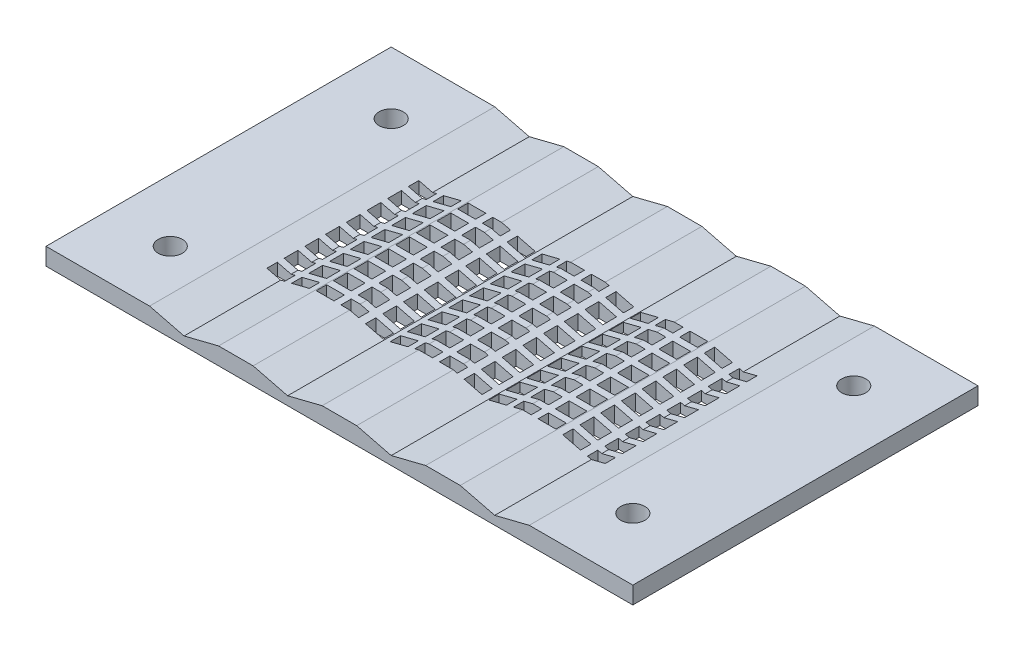
SolidWorks part; units mm, degrees
ref_plane "Front Plane" through (0, 0, 0) normal (0, 0, 1) x (1, 0, 0)
ref_plane "Top Plane" through (0, 0, 0) normal (0, 1, 0) x (1, 0, 0)
ref_plane "Right Plane" through (0, 0, 0) normal (1, 0, 0) x (0, 0, -1)
sketch "Sketch1" plane through (0, 0, 0) normal (0, 1, 0) x (1, 0, 0)
  line L1 (42.5, -25) -> (-42.5, -25)
  line L2 (42.5, -25) -> (42.5, 25)
  line L3 (42.5, 25) -> (-42.5, 25)
  line L4 (-42.5, -25) -> (-42.5, 25)
  line L5 (42.5, -25) -> (-42.5, 25) construction
  line L6 (42.5, 25) -> (-42.5, -25) construction
  point P0 (0, 0)
extrude "Base Plate" add sketch "Sketch1" along normal blind 2.5
sketch "Sketch7" plane through (0, 2.5, 0) normal (0, 1, 0) x (1, 0, 0)
  line L2 (0, 0) -> (-11.5051, 0) construction
  line L3 (-42.5, 25) -> (-42.5, -25) construction
  line L4 (0, 13.9859) -> (0, 0) construction
  line L5 (42.5, 25) -> (-42.5, 25) construction
  circle A0 centre (-33.5, 16) radius 1.75
  circle A1 centre (-33.5, -16) radius 1.75
  circle A2 centre (33.5, -16) radius 1.75
  circle A3 centre (33.5, 16) radius 1.75
  dimension "D1" = 3.5
  dimension "D2" = 9
  dimension "D3" = 9
extrude "Scre Cut" cut sketch "Sketch7" against normal blind 5
sketch "Sketch13" plane through (0, 2.5, 0) normal (0, 1, 0) x (1, 0, 0)
  line L1 (-24.5, 11) -> (24.5, 11)
  line L2 (-24.5, 11) -> (-24.5, -11)
  line L3 (-24.5, -11) -> (24.5, -11)
  line L4 (24.5, 11) -> (24.5, -11)
  line L5 (-24.5, 11) -> (24.5, -11) construction
  line L6 (-24.5, -11) -> (24.5, 11) construction
  line L8 (-42.5, -25) -> (42.5, -25) construction
  line L9 (42.5, -25) -> (42.5, 25) construction
  point P0 (0, 0)
  dimension "D1" = 14
  dimension "D2" = 18
extrude "Cut-Extrude1" cut sketch "Sketch13" against normal blind 10
sketch "Sketch14" plane through (0, 2.5, 0) normal (0, 1, 0) x (1, 0, 0)
  line L0 (-24.5, 0) -> (-22, 0) construction
  line L1 (-24.5, 11) -> (-24.5, -11) construction
  line L2 (-18.3571, -11) -> (-18.3571, -9.5)
  line L3 (-24.5, -11) -> (24.5, -11) construction
  line L4 (-21.9286, 0.5) -> (-21.9286, 2.5)
  line L5 (-24.5, -0.5) -> (-21.9286, -0.5)
  line L6 (-24.5, -0.5) -> (-24.5, 0.5)
  line L7 (-24.5, 0.5) -> (-21.9286, 0.5)
  line L8 (-20.9286, 9.5) -> (-20.9286, 11)
  line L9 (-20.9286, 6.5) -> (-20.9286, 8.5)
  line L10 (-20.9286, 3.5) -> (-20.9286, 5.5)
  line L11 (24.5, 11) -> (-24.5, 11) construction
  line L12 (-21.9286, -11) -> (-20.9286, -11)
  line L13 (-21.9286, -11) -> (-21.9286, -9.5)
  line L14 (-21.9286, 11) -> (-20.9286, 11)
  line L15 (-20.9286, -2.5) -> (-20.9286, -0.5)
  line L16 (-20.9286, -5.5) -> (-20.9286, -3.5)
  line L17 (-20.9286, -8.5) -> (-20.9286, -6.5)
  line L18 (-24.5, 2.5) -> (-24.5, 3.5)
  line L19 (-24.5, 2.5) -> (-21.9286, 2.5)
  line L20 (-24.5, 3.5) -> (-21.9286, 3.5)
  line L21 (-24.5, 5.5) -> (-24.5, 6.5)
  line L22 (-24.5, 5.5) -> (-21.9286, 5.5)
  line L23 (-24.5, 6.5) -> (-21.9286, 6.5)
  line L24 (-24.5, 8.5) -> (-24.5, 9.5)
  line L25 (-24.5, 8.5) -> (-21.9286, 8.5)
  line L26 (-24.5, 9.5) -> (-21.9286, 9.5)
  line L27 (-24.5, -3.5) -> (-21.9286, -3.5)
  line L28 (-24.5, -3.5) -> (-24.5, -2.5)
  line L29 (-24.5, -2.5) -> (-21.9286, -2.5)
  line L30 (-24.5, -6.5) -> (-21.9286, -6.5)
  line L31 (-24.5, -6.5) -> (-24.5, -5.5)
  line L32 (-24.5, -5.5) -> (-21.9286, -5.5)
  line L33 (-24.5, -9.5) -> (-21.9286, -9.5)
  line L34 (-24.5, -9.5) -> (-24.5, -8.5)
  line L35 (-24.5, -8.5) -> (-21.9286, -8.5)
  line L36 (-21.9286, -8.5) -> (-21.9286, -6.5)
  line L37 (-21.9286, -5.5) -> (-21.9286, -3.5)
  line L38 (-21.9286, -2.5) -> (-21.9286, -0.5)
  line L39 (-21.9286, 3.5) -> (-21.9286, 5.5)
  line L40 (-21.9286, 6.5) -> (-21.9286, 8.5)
  line L41 (-21.9286, 9.5) -> (-21.9286, 11)
  line L42 (-21.4286, 11) -> (-21.4286, 9.5) construction
  line L43 (-18.3571, -8.5) -> (-20.9286, -8.5)
  line L44 (-18.3571, -8.5) -> (-18.3571, -6.5)
  line L45 (-18.3571, -9.5) -> (-20.9286, -9.5)
  line L46 (-18.3571, -5.5) -> (-20.9286, -5.5)
  line L47 (-18.3571, -5.5) -> (-18.3571, -3.5)
  line L48 (-18.3571, -6.5) -> (-20.9286, -6.5)
  line L49 (-18.3571, -2.5) -> (-20.9286, -2.5)
  line L50 (-18.3571, -2.5) -> (-18.3571, -0.5)
  line L51 (-18.3571, -3.5) -> (-20.9286, -3.5)
  line L52 (-18.3571, 9.5) -> (-20.9286, 9.5)
  line L53 (-18.3571, 8.5) -> (-20.9286, 8.5)
  line L54 (-18.3571, 0.5) -> (-18.3571, 2.5)
  line L55 (-18.3571, 6.5) -> (-20.9286, 6.5)
  line L56 (-18.3571, 5.5) -> (-20.9286, 5.5)
  line L57 (-18.3571, 3.5) -> (-18.3571, 5.5)
  line L58 (-18.3571, 3.5) -> (-20.9286, 3.5)
  line L59 (-18.3571, 2.5) -> (-20.9286, 2.5)
  line L60 (-18.3571, 9.5) -> (-18.3571, 11)
  line L61 (-20.9286, -11) -> (-20.9286, -9.5)
  line L62 (-18.3571, 0.5) -> (-20.9286, 0.5)
  line L63 (-18.3571, 6.5) -> (-18.3571, 8.5)
  line L64 (-18.3571, -0.5) -> (-20.9286, -0.5)
  line L65 (-20.9286, 0.5) -> (-20.9286, 2.5)
  line L66 (-11.2143, -11) -> (-11.2143, -9.5)
  line L67 (-14.7857, 0.5) -> (-14.7857, 2.5)
  line L68 (-17.3571, -0.5) -> (-14.7857, -0.5)
  line L69 (-17.3571, 0.5) -> (-14.7857, 0.5)
  line L70 (-13.7857, 9.5) -> (-13.7857, 11)
  line L71 (-13.7857, 6.5) -> (-13.7857, 8.5)
  line L72 (-13.7857, 3.5) -> (-13.7857, 5.5)
  line L73 (-14.7857, -11) -> (-13.7857, -11)
  line L74 (-14.7857, -11) -> (-14.7857, -9.5)
  line L75 (-14.7857, 11) -> (-13.7857, 11)
  line L76 (-13.7857, -2.5) -> (-13.7857, -0.5)
  line L77 (-13.7857, -5.5) -> (-13.7857, -3.5)
  line L78 (-13.7857, -8.5) -> (-13.7857, -6.5)
  line L79 (-17.3571, 2.5) -> (-14.7857, 2.5)
  line L80 (-17.3571, 3.5) -> (-14.7857, 3.5)
  line L81 (-17.3571, 5.5) -> (-14.7857, 5.5)
  line L82 (-17.3571, 6.5) -> (-14.7857, 6.5)
  line L83 (-17.3571, 8.5) -> (-14.7857, 8.5)
  line L84 (-17.3571, 9.5) -> (-14.7857, 9.5)
  line L85 (-17.3571, -3.5) -> (-14.7857, -3.5)
  line L86 (-17.3571, -2.5) -> (-14.7857, -2.5)
  line L87 (-17.3571, -6.5) -> (-14.7857, -6.5)
  line L88 (-17.3571, -5.5) -> (-14.7857, -5.5)
  line L89 (-17.3571, -9.5) -> (-14.7857, -9.5)
  line L90 (-17.3571, -8.5) -> (-14.7857, -8.5)
  line L91 (-14.7857, -8.5) -> (-14.7857, -6.5)
  line L92 (-14.7857, -5.5) -> (-14.7857, -3.5)
  line L93 (-14.7857, -2.5) -> (-14.7857, -0.5)
  line L94 (-14.7857, 3.5) -> (-14.7857, 5.5)
  line L95 (-14.7857, 6.5) -> (-14.7857, 8.5)
  line L96 (-14.7857, 9.5) -> (-14.7857, 11)
  line L97 (-11.2143, -8.5) -> (-13.7857, -8.5)
  line L98 (-11.2143, -8.5) -> (-11.2143, -6.5)
  line L99 (-11.2143, -9.5) -> (-13.7857, -9.5)
  line L100 (-11.2143, -5.5) -> (-13.7857, -5.5)
  line L101 (-11.2143, -5.5) -> (-11.2143, -3.5)
  line L102 (-11.2143, -6.5) -> (-13.7857, -6.5)
  line L103 (-11.2143, -2.5) -> (-13.7857, -2.5)
  line L104 (-11.2143, -2.5) -> (-11.2143, -0.5)
  line L105 (-11.2143, -3.5) -> (-13.7857, -3.5)
  line L106 (-11.2143, 9.5) -> (-13.7857, 9.5)
  line L107 (-11.2143, 8.5) -> (-13.7857, 8.5)
  line L108 (-11.2143, 0.5) -> (-11.2143, 2.5)
  line L109 (-11.2143, 6.5) -> (-13.7857, 6.5)
  line L110 (-11.2143, 5.5) -> (-13.7857, 5.5)
  line L111 (-11.2143, 3.5) -> (-11.2143, 5.5)
  line L112 (-11.2143, 3.5) -> (-13.7857, 3.5)
  line L113 (-11.2143, 2.5) -> (-13.7857, 2.5)
  line L114 (-11.2143, 9.5) -> (-11.2143, 11)
  line L115 (-13.7857, -11) -> (-13.7857, -9.5)
  line L116 (-11.2143, 0.5) -> (-13.7857, 0.5)
  line L117 (-11.2143, 6.5) -> (-11.2143, 8.5)
  line L118 (-11.2143, -0.5) -> (-13.7857, -0.5)
  line L119 (-13.7857, 0.5) -> (-13.7857, 2.5)
  line L120 (-17.3571, -11) -> (-17.3571, -9.5)
  line L121 (-17.3571, 11) -> (-18.3571, 11)
  line L122 (-17.3571, 9.5) -> (-17.3571, 11)
  line L123 (-17.3571, 6.5) -> (-17.3571, 8.5)
  line L124 (-17.3571, 3.5) -> (-17.3571, 5.5)
  line L125 (-17.3571, 0.5) -> (-17.3571, 2.5)
  line L126 (-17.3571, -2.5) -> (-17.3571, -0.5)
  line L127 (-17.3571, -5.5) -> (-17.3571, -3.5)
  line L128 (-17.3571, -8.5) -> (-17.3571, -6.5)
  line L129 (-17.3571, -11) -> (-18.3571, -11)
  line L130 (-7.6429, -11) -> (-7.6429, -9.5)
  line L131 (-10.2143, 9.5) -> (-10.2143, 11)
  line L132 (-10.2143, 6.5) -> (-10.2143, 8.5)
  line L133 (-10.2143, 3.5) -> (-10.2143, 5.5)
  line L134 (-11.2143, -11) -> (-10.2143, -11)
  line L135 (-10.2143, -2.5) -> (-10.2143, -0.5)
  line L136 (-10.2143, -5.5) -> (-10.2143, -3.5)
  line L137 (-10.2143, -8.5) -> (-10.2143, -6.5)
  line L138 (-7.6429, -8.5) -> (-10.2143, -8.5)
  line L139 (-7.6429, -8.5) -> (-7.6429, -6.5)
  line L140 (-7.6429, -9.5) -> (-10.2143, -9.5)
  line L141 (-7.6429, -5.5) -> (-10.2143, -5.5)
  line L142 (-7.6429, -5.5) -> (-7.6429, -3.5)
  line L143 (-7.6429, -6.5) -> (-10.2143, -6.5)
  line L144 (-7.6429, -2.5) -> (-10.2143, -2.5)
  line L145 (-7.6429, -2.5) -> (-7.6429, -0.5)
  line L146 (-7.6429, -3.5) -> (-10.2143, -3.5)
  line L147 (-7.6429, 9.5) -> (-10.2143, 9.5)
  line L148 (-7.6429, 8.5) -> (-10.2143, 8.5)
  line L149 (-7.6429, 0.5) -> (-7.6429, 2.5)
  line L150 (-7.6429, 6.5) -> (-10.2143, 6.5)
  line L151 (-7.6429, 5.5) -> (-10.2143, 5.5)
  line L152 (-7.6429, 3.5) -> (-7.6429, 5.5)
  line L153 (-7.6429, 3.5) -> (-10.2143, 3.5)
  line L154 (-7.6429, 2.5) -> (-10.2143, 2.5)
  line L155 (-7.6429, 9.5) -> (-7.6429, 11)
  line L156 (-10.2143, -11) -> (-10.2143, -9.5)
  line L157 (-7.6429, 0.5) -> (-10.2143, 0.5)
  line L158 (-7.6429, 6.5) -> (-7.6429, 8.5)
  line L159 (-7.6429, -0.5) -> (-10.2143, -0.5)
  line L160 (-10.2143, 0.5) -> (-10.2143, 2.5)
  line L161 (-11.2143, 11) -> (-10.2143, 11)
  line L162 (-4.0714, -11) -> (-4.0714, -9.5)
  line L163 (-6.6429, 9.5) -> (-6.6429, 11)
  line L164 (-6.6429, 6.5) -> (-6.6429, 8.5)
  line L165 (-6.6429, 3.5) -> (-6.6429, 5.5)
  line L166 (-7.6429, -11) -> (-6.6429, -11)
  line L167 (-6.6429, -2.5) -> (-6.6429, -0.5)
  line L168 (-6.6429, -5.5) -> (-6.6429, -3.5)
  line L169 (-6.6429, -8.5) -> (-6.6429, -6.5)
  line L170 (-4.0714, -8.5) -> (-6.6429, -8.5)
  line L171 (-4.0714, -8.5) -> (-4.0714, -6.5)
  line L172 (-4.0714, -9.5) -> (-6.6429, -9.5)
  line L173 (-4.0714, -5.5) -> (-6.6429, -5.5)
  line L174 (-4.0714, -5.5) -> (-4.0714, -3.5)
  line L175 (-4.0714, -6.5) -> (-6.6429, -6.5)
  line L176 (-4.0714, -2.5) -> (-6.6429, -2.5)
  line L177 (-4.0714, -2.5) -> (-4.0714, -0.5)
  line L178 (-4.0714, -3.5) -> (-6.6429, -3.5)
  line L179 (-4.0714, 9.5) -> (-6.6429, 9.5)
  line L180 (-4.0714, 8.5) -> (-6.6429, 8.5)
  line L181 (-4.0714, 0.5) -> (-4.0714, 2.5)
  line L182 (-4.0714, 6.5) -> (-6.6429, 6.5)
  line L183 (-4.0714, 5.5) -> (-6.6429, 5.5)
  line L184 (-4.0714, 3.5) -> (-4.0714, 5.5)
  line L185 (-4.0714, 3.5) -> (-6.6429, 3.5)
  line L186 (-4.0714, 2.5) -> (-6.6429, 2.5)
  line L187 (-4.0714, 9.5) -> (-4.0714, 11)
  line L188 (-6.6429, -11) -> (-6.6429, -9.5)
  line L189 (-4.0714, 0.5) -> (-6.6429, 0.5)
  line L190 (-4.0714, 6.5) -> (-4.0714, 8.5)
  line L191 (-4.0714, -0.5) -> (-6.6429, -0.5)
  line L192 (-6.6429, 0.5) -> (-6.6429, 2.5)
  line L193 (-7.6429, 11) -> (-6.6429, 11)
  line L194 (-0.5, -11) -> (-0.5, -9.5)
  line L195 (-3.0714, 9.5) -> (-3.0714, 11)
  line L196 (-3.0714, 6.5) -> (-3.0714, 8.5)
  line L197 (-3.0714, 3.5) -> (-3.0714, 5.5)
  line L198 (-4.0714, -11) -> (-3.0714, -11)
  line L199 (-3.0714, -2.5) -> (-3.0714, -0.5)
  line L200 (-3.0714, -5.5) -> (-3.0714, -3.5)
  line L201 (-3.0714, -8.5) -> (-3.0714, -6.5)
  line L202 (-0.5, -8.5) -> (-3.0714, -8.5)
  line L203 (-0.5, -8.5) -> (-0.5, -6.5)
  line L204 (-0.5, -9.5) -> (-3.0714, -9.5)
  line L205 (-0.5, -5.5) -> (-3.0714, -5.5)
  line L206 (-0.5, -5.5) -> (-0.5, -3.5)
  line L207 (-0.5, -6.5) -> (-3.0714, -6.5)
  line L208 (-0.5, -2.5) -> (-3.0714, -2.5)
  line L209 (-0.5, -2.5) -> (-0.5, -0.5)
  line L210 (-0.5, -3.5) -> (-3.0714, -3.5)
  line L211 (-0.5, 9.5) -> (-3.0714, 9.5)
  line L212 (-0.5, 8.5) -> (-3.0714, 8.5)
  line L213 (-0.5, 0.5) -> (-0.5, 2.5)
  line L214 (-0.5, 6.5) -> (-3.0714, 6.5)
  line L215 (-0.5, 5.5) -> (-3.0714, 5.5)
  line L216 (-0.5, 3.5) -> (-0.5, 5.5)
  line L217 (-0.5, 3.5) -> (-3.0714, 3.5)
  line L218 (-0.5, 2.5) -> (-3.0714, 2.5)
  line L219 (-0.5, 9.5) -> (-0.5, 11)
  line L220 (-3.0714, -11) -> (-3.0714, -9.5)
  line L221 (-0.5, 0.5) -> (-3.0714, 0.5)
  line L222 (-0.5, 6.5) -> (-0.5, 8.5)
  line L223 (-0.5, -0.5) -> (-3.0714, -0.5)
  line L224 (-3.0714, 0.5) -> (-3.0714, 2.5)
  line L225 (-4.0714, 11) -> (-3.0714, 11)
  line L226 (3.0714, -11) -> (3.0714, -9.5)
  line L227 (0.5, 9.5) -> (0.5, 11)
  line L228 (0.5, 6.5) -> (0.5, 8.5)
  line L229 (0.5, 3.5) -> (0.5, 5.5)
  line L230 (-0.5, -11) -> (0.5, -11)
  line L231 (0.5, -2.5) -> (0.5, -0.5)
  line L232 (0.5, -5.5) -> (0.5, -3.5)
  line L233 (0.5, -8.5) -> (0.5, -6.5)
  line L234 (3.0714, -8.5) -> (0.5, -8.5)
  line L235 (3.0714, -8.5) -> (3.0714, -6.5)
  line L236 (3.0714, -9.5) -> (0.5, -9.5)
  line L237 (3.0714, -5.5) -> (0.5, -5.5)
  line L238 (3.0714, -5.5) -> (3.0714, -3.5)
  line L239 (3.0714, -6.5) -> (0.5, -6.5)
  line L240 (3.0714, -2.5) -> (0.5, -2.5)
  line L241 (3.0714, -2.5) -> (3.0714, -0.5)
  line L242 (3.0714, -3.5) -> (0.5, -3.5)
  line L243 (3.0714, 9.5) -> (0.5, 9.5)
  line L244 (3.0714, 8.5) -> (0.5, 8.5)
  line L245 (3.0714, 0.5) -> (3.0714, 2.5)
  line L246 (3.0714, 6.5) -> (0.5, 6.5)
  line L247 (3.0714, 5.5) -> (0.5, 5.5)
  line L248 (3.0714, 3.5) -> (3.0714, 5.5)
  line L249 (3.0714, 3.5) -> (0.5, 3.5)
  line L250 (3.0714, 2.5) -> (0.5, 2.5)
  line L251 (3.0714, 9.5) -> (3.0714, 11)
  line L252 (0.5, -11) -> (0.5, -9.5)
  line L253 (3.0714, 0.5) -> (0.5, 0.5)
  line L254 (3.0714, 6.5) -> (3.0714, 8.5)
  line L255 (3.0714, -0.5) -> (0.5, -0.5)
  line L256 (0.5, 0.5) -> (0.5, 2.5)
  line L257 (-0.5, 11) -> (0.5, 11)
  line L258 (6.6429, -11) -> (6.6429, -9.5)
  line L259 (4.0714, 9.5) -> (4.0714, 11)
  line L260 (4.0714, 6.5) -> (4.0714, 8.5)
  line L261 (4.0714, 3.5) -> (4.0714, 5.5)
  line L262 (3.0714, -11) -> (4.0714, -11)
  line L263 (4.0714, -2.5) -> (4.0714, -0.5)
  line L264 (4.0714, -5.5) -> (4.0714, -3.5)
  line L265 (4.0714, -8.5) -> (4.0714, -6.5)
  line L266 (6.6429, -8.5) -> (4.0714, -8.5)
  line L267 (6.6429, -8.5) -> (6.6429, -6.5)
  line L268 (6.6429, -9.5) -> (4.0714, -9.5)
  line L269 (6.6429, -5.5) -> (4.0714, -5.5)
  line L270 (6.6429, -5.5) -> (6.6429, -3.5)
  line L271 (6.6429, -6.5) -> (4.0714, -6.5)
  line L272 (6.6429, -2.5) -> (4.0714, -2.5)
  line L273 (6.6429, -2.5) -> (6.6429, -0.5)
  line L274 (6.6429, -3.5) -> (4.0714, -3.5)
  line L275 (6.6429, 9.5) -> (4.0714, 9.5)
  line L276 (6.6429, 8.5) -> (4.0714, 8.5)
  line L277 (6.6429, 0.5) -> (6.6429, 2.5)
  line L278 (6.6429, 6.5) -> (4.0714, 6.5)
  line L279 (6.6429, 5.5) -> (4.0714, 5.5)
  line L280 (6.6429, 3.5) -> (6.6429, 5.5)
  line L281 (6.6429, 3.5) -> (4.0714, 3.5)
  line L282 (6.6429, 2.5) -> (4.0714, 2.5)
  line L283 (6.6429, 9.5) -> (6.6429, 11)
  line L284 (4.0714, -11) -> (4.0714, -9.5)
  line L285 (6.6429, 0.5) -> (4.0714, 0.5)
  line L286 (6.6429, 6.5) -> (6.6429, 8.5)
  line L287 (6.6429, -0.5) -> (4.0714, -0.5)
  line L288 (4.0714, 0.5) -> (4.0714, 2.5)
  line L289 (3.0714, 11) -> (4.0714, 11)
  line L290 (10.2143, -11) -> (10.2143, -9.5)
  line L291 (7.6429, 9.5) -> (7.6429, 11)
  line L292 (7.6429, 6.5) -> (7.6429, 8.5)
  line L293 (7.6429, 3.5) -> (7.6429, 5.5)
  line L294 (6.6429, -11) -> (7.6429, -11)
  line L295 (7.6429, -2.5) -> (7.6429, -0.5)
  line L296 (7.6429, -5.5) -> (7.6429, -3.5)
  line L297 (7.6429, -8.5) -> (7.6429, -6.5)
  line L298 (10.2143, -8.5) -> (7.6429, -8.5)
  line L299 (10.2143, -8.5) -> (10.2143, -6.5)
  line L300 (10.2143, -9.5) -> (7.6429, -9.5)
  line L301 (10.2143, -5.5) -> (7.6429, -5.5)
  line L302 (10.2143, -5.5) -> (10.2143, -3.5)
  line L303 (10.2143, -6.5) -> (7.6429, -6.5)
  line L304 (10.2143, -2.5) -> (7.6429, -2.5)
  line L305 (10.2143, -2.5) -> (10.2143, -0.5)
  line L306 (10.2143, -3.5) -> (7.6429, -3.5)
  line L307 (10.2143, 9.5) -> (7.6429, 9.5)
  line L308 (10.2143, 8.5) -> (7.6429, 8.5)
  line L309 (10.2143, 0.5) -> (10.2143, 2.5)
  line L310 (10.2143, 6.5) -> (7.6429, 6.5)
  line L311 (10.2143, 5.5) -> (7.6429, 5.5)
  line L312 (10.2143, 3.5) -> (10.2143, 5.5)
  line L313 (10.2143, 3.5) -> (7.6429, 3.5)
  line L314 (10.2143, 2.5) -> (7.6429, 2.5)
  line L315 (10.2143, 9.5) -> (10.2143, 11)
  line L316 (7.6429, -11) -> (7.6429, -9.5)
  line L317 (10.2143, 0.5) -> (7.6429, 0.5)
  line L318 (10.2143, 6.5) -> (10.2143, 8.5)
  line L319 (10.2143, -0.5) -> (7.6429, -0.5)
  line L320 (7.6429, 0.5) -> (7.6429, 2.5)
  line L321 (6.6429, 11) -> (7.6429, 11)
  line L322 (13.7857, -11) -> (13.7857, -9.5)
  line L323 (11.2143, 9.5) -> (11.2143, 11)
  line L324 (11.2143, 6.5) -> (11.2143, 8.5)
  line L325 (11.2143, 3.5) -> (11.2143, 5.5)
  line L326 (10.2143, -11) -> (11.2143, -11)
  line L327 (11.2143, -2.5) -> (11.2143, -0.5)
  line L328 (11.2143, -5.5) -> (11.2143, -3.5)
  line L329 (11.2143, -8.5) -> (11.2143, -6.5)
  line L330 (13.7857, -8.5) -> (11.2143, -8.5)
  line L331 (13.7857, -8.5) -> (13.7857, -6.5)
  line L332 (13.7857, -9.5) -> (11.2143, -9.5)
  line L333 (13.7857, -5.5) -> (11.2143, -5.5)
  line L334 (13.7857, -5.5) -> (13.7857, -3.5)
  line L335 (13.7857, -6.5) -> (11.2143, -6.5)
  line L336 (13.7857, -2.5) -> (11.2143, -2.5)
  line L337 (13.7857, -2.5) -> (13.7857, -0.5)
  line L338 (13.7857, -3.5) -> (11.2143, -3.5)
  line L339 (13.7857, 9.5) -> (11.2143, 9.5)
  line L340 (13.7857, 8.5) -> (11.2143, 8.5)
  line L341 (13.7857, 0.5) -> (13.7857, 2.5)
  line L342 (13.7857, 6.5) -> (11.2143, 6.5)
  line L343 (13.7857, 5.5) -> (11.2143, 5.5)
  line L344 (13.7857, 3.5) -> (13.7857, 5.5)
  line L345 (13.7857, 3.5) -> (11.2143, 3.5)
  line L346 (13.7857, 2.5) -> (11.2143, 2.5)
  line L347 (13.7857, 9.5) -> (13.7857, 11)
  line L348 (11.2143, -11) -> (11.2143, -9.5)
  line L349 (13.7857, 0.5) -> (11.2143, 0.5)
  line L350 (13.7857, 6.5) -> (13.7857, 8.5)
  line L351 (13.7857, -0.5) -> (11.2143, -0.5)
  line L352 (11.2143, 0.5) -> (11.2143, 2.5)
  line L353 (10.2143, 11) -> (11.2143, 11)
  line L354 (17.3571, -11) -> (17.3571, -9.5)
  line L355 (14.7857, 9.5) -> (14.7857, 11)
  line L356 (14.7857, 6.5) -> (14.7857, 8.5)
  line L357 (14.7857, 3.5) -> (14.7857, 5.5)
  line L358 (13.7857, -11) -> (14.7857, -11)
  line L359 (14.7857, -2.5) -> (14.7857, -0.5)
  line L360 (14.7857, -5.5) -> (14.7857, -3.5)
  line L361 (14.7857, -8.5) -> (14.7857, -6.5)
  line L362 (17.3571, -8.5) -> (14.7857, -8.5)
  line L363 (17.3571, -8.5) -> (17.3571, -6.5)
  line L364 (17.3571, -9.5) -> (14.7857, -9.5)
  line L365 (17.3571, -5.5) -> (14.7857, -5.5)
  line L366 (17.3571, -5.5) -> (17.3571, -3.5)
  line L367 (17.3571, -6.5) -> (14.7857, -6.5)
  line L368 (17.3571, -2.5) -> (14.7857, -2.5)
  line L369 (17.3571, -2.5) -> (17.3571, -0.5)
  line L370 (17.3571, -3.5) -> (14.7857, -3.5)
  line L371 (17.3571, 9.5) -> (14.7857, 9.5)
  line L372 (17.3571, 8.5) -> (14.7857, 8.5)
  line L373 (17.3571, 0.5) -> (17.3571, 2.5)
  line L374 (17.3571, 6.5) -> (14.7857, 6.5)
  line L375 (17.3571, 5.5) -> (14.7857, 5.5)
  line L376 (17.3571, 3.5) -> (17.3571, 5.5)
  line L377 (17.3571, 3.5) -> (14.7857, 3.5)
  line L378 (17.3571, 2.5) -> (14.7857, 2.5)
  line L379 (17.3571, 9.5) -> (17.3571, 11)
  line L380 (14.7857, -11) -> (14.7857, -9.5)
  line L381 (17.3571, 0.5) -> (14.7857, 0.5)
  line L382 (17.3571, 6.5) -> (17.3571, 8.5)
  line L383 (17.3571, -0.5) -> (14.7857, -0.5)
  line L384 (14.7857, 0.5) -> (14.7857, 2.5)
  line L385 (13.7857, 11) -> (14.7857, 11)
  line L386 (20.9286, -11) -> (20.9286, -9.5)
  line L387 (18.3571, 9.5) -> (18.3571, 11)
  line L388 (18.3571, 6.5) -> (18.3571, 8.5)
  line L389 (18.3571, 3.5) -> (18.3571, 5.5)
  line L390 (17.3571, -11) -> (18.3571, -11)
  line L391 (18.3571, -2.5) -> (18.3571, -0.5)
  line L392 (18.3571, -5.5) -> (18.3571, -3.5)
  line L393 (18.3571, -8.5) -> (18.3571, -6.5)
  line L394 (20.9286, -8.5) -> (18.3571, -8.5)
  line L395 (20.9286, -8.5) -> (20.9286, -6.5)
  line L396 (20.9286, -9.5) -> (18.3571, -9.5)
  line L397 (20.9286, -5.5) -> (18.3571, -5.5)
  line L398 (20.9286, -5.5) -> (20.9286, -3.5)
  line L399 (20.9286, -6.5) -> (18.3571, -6.5)
  line L400 (20.9286, -2.5) -> (18.3571, -2.5)
  line L401 (20.9286, -2.5) -> (20.9286, -0.5)
  line L402 (20.9286, -3.5) -> (18.3571, -3.5)
  line L403 (20.9286, 9.5) -> (18.3571, 9.5)
  line L404 (20.9286, 8.5) -> (18.3571, 8.5)
  line L405 (20.9286, 0.5) -> (20.9286, 2.5)
  line L406 (20.9286, 6.5) -> (18.3571, 6.5)
  line L407 (20.9286, 5.5) -> (18.3571, 5.5)
  line L408 (20.9286, 3.5) -> (20.9286, 5.5)
  line L409 (20.9286, 3.5) -> (18.3571, 3.5)
  line L410 (20.9286, 2.5) -> (18.3571, 2.5)
  line L411 (20.9286, 9.5) -> (20.9286, 11)
  line L412 (18.3571, -11) -> (18.3571, -9.5)
  line L413 (20.9286, 0.5) -> (18.3571, 0.5)
  line L414 (20.9286, 6.5) -> (20.9286, 8.5)
  line L415 (20.9286, -0.5) -> (18.3571, -0.5)
  line L416 (18.3571, 0.5) -> (18.3571, 2.5)
  line L417 (17.3571, 11) -> (18.3571, 11)
  line L418 (24.5, -6.5) -> (24.5, -5.5)
  line L419 (21.9286, 9.5) -> (21.9286, 11)
  line L420 (21.9286, 6.5) -> (21.9286, 8.5)
  line L421 (21.9286, 3.5) -> (21.9286, 5.5)
  line L422 (20.9286, -11) -> (21.9286, -11)
  line L423 (21.9286, -2.5) -> (21.9286, -0.5)
  line L424 (21.9286, -5.5) -> (21.9286, -3.5)
  line L425 (21.9286, -8.5) -> (21.9286, -6.5)
  line L426 (24.5, -8.5) -> (21.9286, -8.5)
  line L427 (24.5, -3.5) -> (24.5, -2.5)
  line L428 (24.5, -9.5) -> (21.9286, -9.5)
  line L429 (24.5, -5.5) -> (21.9286, -5.5)
  line L430 (24.5, -0.5) -> (24.5, 0.5)
  line L431 (24.5, -6.5) -> (21.9286, -6.5)
  line L432 (24.5, -2.5) -> (21.9286, -2.5)
  line L433 (24.5, 8.5) -> (24.5, 9.5)
  line L434 (24.5, -3.5) -> (21.9286, -3.5)
  line L435 (24.5, 9.5) -> (21.9286, 9.5)
  line L436 (24.5, 8.5) -> (21.9286, 8.5)
  line L437 (24.5, 5.5) -> (24.5, 6.5)
  line L438 (24.5, 6.5) -> (21.9286, 6.5)
  line L439 (24.5, 5.5) -> (21.9286, 5.5)
  line L440 (24.5, 2.5) -> (24.5, 3.5)
  line L441 (24.5, 3.5) -> (21.9286, 3.5)
  line L442 (24.5, 2.5) -> (21.9286, 2.5)
  line L443 (24.5, -11) -> (24.5, 11) construction
  line L444 (21.9286, -11) -> (21.9286, -9.5)
  line L445 (24.5, 0.5) -> (21.9286, 0.5)
  line L447 (24.5, -0.5) -> (21.9286, -0.5)
  line L448 (21.9286, 0.5) -> (21.9286, 2.5)
  line L449 (20.9286, 11) -> (21.9286, 11)
  line L451 (24.5, -9.5) -> (24.5, -8.5)
  line L454 (24.5, -11) -> (24.5, -9.5) [skipped]
  line L455 (24.5, -8.5) -> (24.5, -6.5) [skipped]
  line L456 (24.5, -5.5) -> (24.5, -3.5) [skipped]
  line L457 (24.5, -2.5) -> (24.5, -0.5) [skipped]
  line L458 (24.5, 9.5) -> (24.5, 11) [skipped]
  line L459 (24.5, 6.5) -> (24.5, 8.5) [skipped]
  line L460 (24.5, 3.5) -> (24.5, 5.5) [skipped]
  line L461 (24.5, 0.5) -> (24.5, 2.5) [skipped]
  dimension "D1" = 1
  dimension "D2" = 1
  dimension "D6" = 2
  dimension "D7" = 11
  dimension "D8" = 1
  dimension "D4" = 4
  dimension "D5" = 4
extrude "Boss-Extrude1" add sketch "Sketch14" against normal up to surface (2.5 mm away) up to face at (0, 0, 0)
sketch "Sketch15" plane through (-42.5, 0, -25) normal (0, -1, 0) x (1, 0, 0)
  line L0 (42.5, 0) -> (42.5, 50) construction
  line L1 (85, 0) -> (0, 0) construction
  line L2 (0, 0) -> (0, 50) construction
  line L3 (0, 25) -> (42.5, 25) construction
  circle A0 centre (9, 9) radius 5
  circle A1 centre (9, 41) radius 5
  circle A2 centre (76, 41) radius 5
  circle A3 centre (76, 9) radius 5
  dimension "D1" = 10
extrude "Boss-Extrude3" add sketch "Sketch15" along normal blind 4
sketch "Sketch18" plane through (0, 0, 0) normal (0, 1, 0) x (1, 0, 0)
  line L0 (0, 0) -> (0, -29.8583) construction
  line L2 (-49.7998, 0) -> (0, 0) construction
  circle A0 centre (-33.5, 16) radius 1.75
  circle A1 centre (-33.5, 16) radius 1.75 construction
  circle A2 centre (-33.5, -16) radius 1.75
  circle A3 centre (33.5, 16) radius 1.75
  circle A4 centre (33.5, -16) radius 1.75
extrude "Cut-Extrude4" cut sketch "Sketch18" against normal up to surface (4 mm away) up to face at (-33.5, -4, -21)
sketch "Sketch19" plane through (0, -4, 0) normal (0, -1, 0) x (1, 0, 0)
  line L0 (0, 0) -> (0, -22.785) construction
  line L1 (-33.5, -12.7668) -> (-36.3, -14.3834)
  line L2 (-36.3, -14.3834) -> (-36.3, -17.6166)
  line L3 (-36.3, -17.6166) -> (-33.5, -19.2332)
  line L4 (-33.5, -19.2332) -> (-30.7, -17.6166)
  line L5 (-30.7, -17.6166) -> (-30.7, -14.3834)
  line L6 (-30.7, -14.3834) -> (-33.5, -12.7668)
  line L7 (-30.7, 14.3834) -> (-33.5, 12.7668)
  line L8 (-38.1664, 0) -> (0, 0) construction
  line L9 (-30.7, 17.6166) -> (-30.7, 14.3834)
  line L10 (-33.5, 19.2332) -> (-30.7, 17.6166)
  line L11 (-36.3, 17.6166) -> (-33.5, 19.2332)
  line L12 (-36.3, 14.3834) -> (-36.3, 17.6166)
  line L13 (-33.5, 12.7668) -> (-36.3, 14.3834)
  line L14 (30.7, -14.3834) -> (33.5, -12.7668)
  line L15 (30.7, -17.6166) -> (30.7, -14.3834)
  line L16 (33.5, -19.2332) -> (30.7, -17.6166)
  line L17 (36.3, -17.6166) -> (33.5, -19.2332)
  line L18 (36.3, -14.3834) -> (36.3, -17.6166)
  line L19 (33.5, -12.7668) -> (36.3, -14.3834)
  line L20 (33.5, 12.7668) -> (36.3, 14.3834)
  line L21 (36.3, 14.3834) -> (36.3, 17.6166)
  line L22 (36.3, 17.6166) -> (33.5, 19.2332)
  line L23 (33.5, 19.2332) -> (30.7, 17.6166)
  line L24 (30.7, 17.6166) -> (30.7, 14.3834)
  line L25 (30.7, 14.3834) -> (33.5, 12.7668)
  circle A2 centre (-33.5, -16) radius 2.8 construction
  circle A3 centre (-33.5, 16) radius 2.8 construction
  circle A4 centre (33.5, -16) radius 2.8 construction
  circle A5 centre (33.5, 16) radius 2.8 construction
  dimension "D1" = 5.6
extrude "M3 Nut" cut sketch "Sketch19" against normal blind 3
sketch "Sketch20" plane through (0, 0, -25) normal (0, 0, -1) x (-1, 0, 0)
  line L0 (-42.5, 2.5) -> (42.5, 2.5) construction
  line L1 (2.5, 2.5) -> (12.5, 2.5)
  line L2 (12.5, 2.5) -> (7.5, 1.25)
  line L3 (7.5, 1.25) -> (2.5, 2.5)
  line L4 (7.5, 2.5) -> (7.5, 1.25) construction
  line L5 (15, 2.5) -> (15, 1.8239) construction
  line L6 (17.5, 2.5) -> (22.5, 1.25)
  line L7 (0, 2.5) -> (0, 3.5097) construction
  line L8 (27.5, 2.5) -> (17.5, 2.5)
  line L9 (22.5, 1.25) -> (27.5, 2.5)
  line L10 (-27.5, 2.5) -> (-17.5, 2.5)
  line L11 (-22.5, 1.25) -> (-27.5, 2.5)
  line L12 (-17.5, 2.5) -> (-22.5, 1.25)
  line L13 (-12.5, 2.5) -> (-7.5, 1.25)
  line L14 (-7.5, 1.25) -> (-2.5, 2.5)
  line L15 (-2.5, 2.5) -> (-12.5, 2.5)
  dimension "D1" = 1.25
  dimension "D2" = 2.5
  dimension "D3" = 10
  dimension "D4" = 2.5
extrude "Cut-Extrude5" cut sketch "Sketch20" against normal up to surface (50 mm away)
